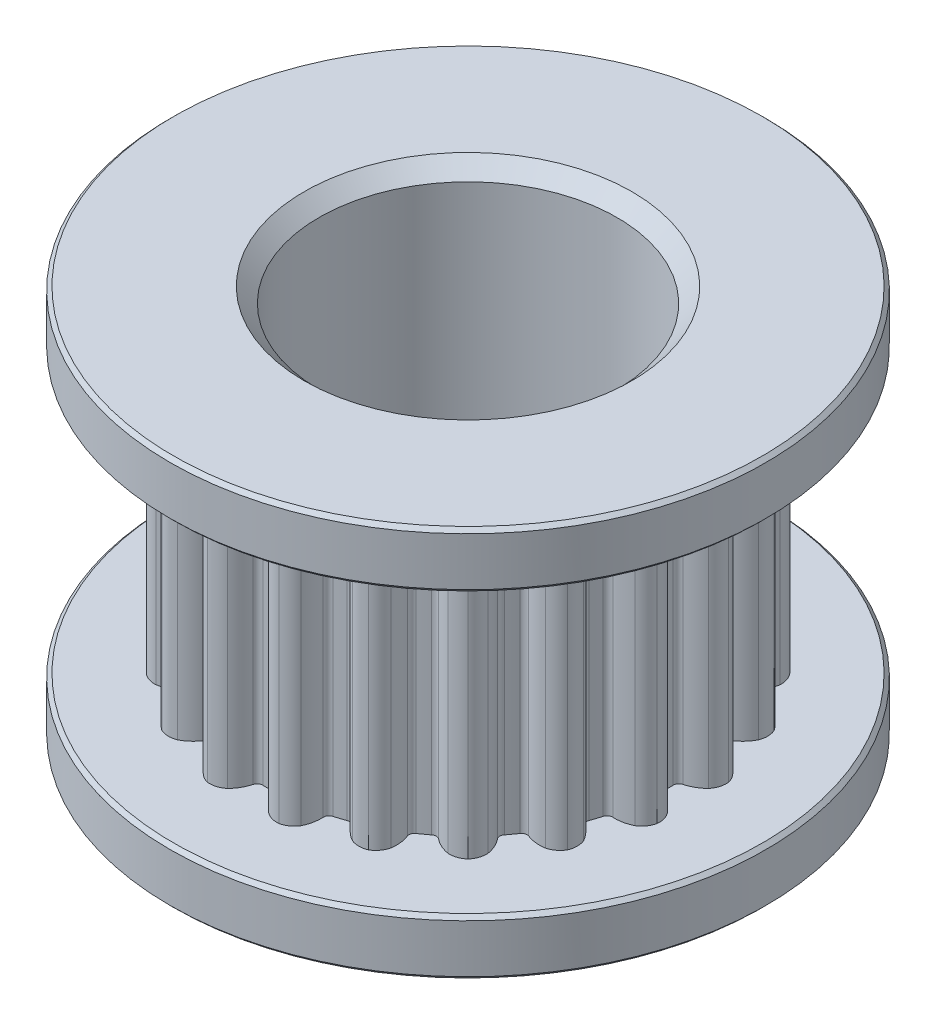
SolidWorks part; units mm, degrees
material "6061 Alloy"
ref_plane "Front Plane" through (0, 0, 0) normal (0, 0, 1) x (1, 0, 0)
ref_plane "Top Plane" through (0, 0, 0) normal (0, 1, 0) x (1, 0, 0)
ref_plane "Right Plane" through (0, 0, 0) normal (1, 0, 0) x (0, 0, -1)
sketch "BodyS" plane through (0, 0, 0) normal (0, 0, 1) x (1, 0, 0)
  line L0 (6.11, -3.75) -> (6.11, 3.75)
  line L1 (6.11, 3.75) -> (8, 3.75)
  line L2 (8, 3.75) -> (8, 5.25)
  line L3 (8, 5.25) -> (4, 5.25)
  line L4 (4, 5.25) -> (4, 2.25)
  line L5 (4, 2.25) -> (3.5, 2.25)
  line L6 (3.5, 2.25) -> (3.5, -2.25)
  line L7 (3.5, -2.25) -> (4, -2.25)
  line L8 (4, -2.25) -> (4, -5.25)
  line L9 (4, -5.25) -> (8, -5.25)
  line L10 (8, -5.25) -> (8, -3.75)
  line L11 (8, -3.75) -> (6.11, -3.75)
  line L12 (0, 0) -> (3.5, 0) construction
  line L13 (0, 5.25) -> (0, -5.25) construction
  dimension "BearingOD" = 8
  dimension "Height" = 10.5
  dimension "FlangeHeight" = 1.5
  dimension "BearingHeight" = 3
  dimension "BearingRestDiaControl" = 0.5
  dimension "RefBodyInnerDiameter" = 7
  dimension "FlangeDiaControl" = 4
  dimension "RefFlangeDia" = 16
  dimension "BeltPathDiaControl" = 2.11
  dimension "RefBeltPathDia" = 12.22
revolve "Body" add sketch "BodyS" angle 360 about L13
sketch "GT2ProfileS" plane through (0, 0, 0) normal (0, 1, 0) x (1, 0, 0)
  line L1 (0, -6.11) -> (0, -5.36) construction
  line L2 (-0.9955, -6.0283) -> (-0.8733, -5.2884) construction
  line L3 (0, 0) -> (-0.8733, -5.2884) construction
  line L4 (0.9955, -6.0283) -> (0, 0) construction
  arc A3 (0.2997, -5.4688) -> (0.1507, -5.3579) centre (0.1549, -5.5078) ccw
  arc A4 (-0.9955, -6.0283) -> (0.9955, -6.0283) centre (0, 0) ccw
  arc A5 (-0.2997, -5.4688) -> (-0.1507, -5.3579) centre (-0.1549, -5.5078) cw
  arc A6 (-0.2997, -5.4688) -> (-0.5497, -5.907) centre (-1.2653, -5.2085) cw
  circle A7 centre (0, 0) radius 6.11 construction
  arc A8 (-0.1507, -5.3579) -> (0.1507, -5.3579) centre (0, 0) ccw
  arc A9 (-0.5497, -5.907) -> (-0.9955, -6.0283) centre (-0.9051, -5.4808) cw
  arc A10 (0.2997, -5.4688) -> (0.5497, -5.907) centre (1.2653, -5.2085) ccw
  arc A11 (0.5497, -5.907) -> (0.9955, -6.0283) centre (0.9051, -5.4808) ccw
  circle A12 centre (0, 0) radius 5.36 construction
  dimension "BottomRadius" = 0.15
  dimension "MidRadius" = 1
  dimension "TopRadius" = 0.555
  dimension "Height" = 0.75
  dimension "XDistMidRadius" = 0.4
  dimension "ArcLengthAngle" = 18.755
  dimension "ArcLength" = 2
sketch "ThruBoreS" plane through (0, 0, 0) normal (0, 1, 0) x (1, 0, 0)
  circle A0 centre (0, 0) radius 4
  circle A2 centre (0, 0) radius 4 construction
extrude "ThruBore" cut sketch "ThruBoreS" against normal through all both and the other way through all
extrude "GT2Profile" cut sketch "GT2ProfileS" against normal up to surface and the other way up to surface up to face at (0, -3.75, 6.11) other way up to face at (0, 3.75, 8)
pattern_circular "GT2 Groove CP" count 20 over 360 about axis through (0, 0, 0) along (0, 1, 0) of "GT2Profile"
chamfer "InnerC" distance 0.4 angle 45 2 edges at (0, -5.25, 4) (0, 5.25, 4)
chamfer "OuterC" distance 0.1 angle 45 4 edges at (0, -5.25, 8) (0, -3.75, 8) (0, 3.75, 8) (0, 5.25, 8)
equation "\"NumTeeth@GT2 Groove CP\"=int(360/\"ArcLengthAngle@GT2ProfileS\")+1"
